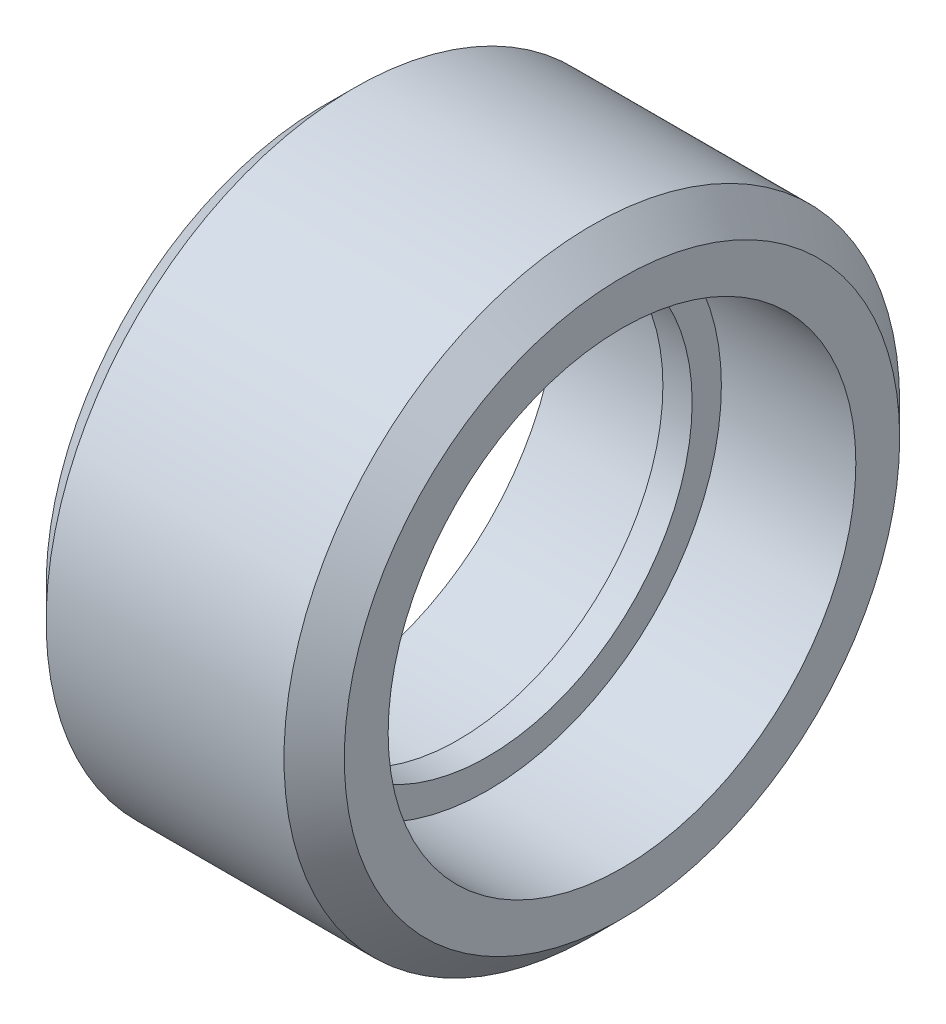
SolidWorks part; units mm, degrees
ref_plane "Front Plane" through (0, 0, 0) normal (0, 0, 1) x (1, 0, 0)
ref_plane "Top Plane" through (0, 0, 0) normal (0, 1, 0) x (1, 0, 0)
ref_plane "Right Plane" through (0, 0, 0) normal (1, 0, 0) x (0, 0, -1)
sketch "Sketch1" plane through (0, 0, 0) normal (0, 0, 1) x (1, 0, 0)
  line L0 (0, 0) -> (0, 8) construction
  line L1 (0, -55) -> (0, 55) construction
  line L2 (0, 7) -> (-0.5, 7)
  line L3 (-0.5, 7) -> (-0.5, 8)
  line L4 (-0.5, 8) -> (-5.1, 8)
  line L5 (-5.1, 8) -> (-5.1, 9.5)
  line L6 (-5.1, 9.5) -> (-4.0686, 10.5314)
  line L7 (-4.0686, 10.5314) -> (0, 10.5314)
  line L8 (0, 10.5314) -> (0, 7)
  line L9 (55, 0) -> (-55, 0) construction
  line L10 (0, 0) -> (-8.8433, 0) construction
  point P5 (0, 7)
  dimension "D1" = 7
  dimension "D2" = 5.1
  dimension "D3" = 4.0686
  dimension "D4" = 45
  dimension "D5" = 8
revolve "Revolve1" add sketch "Sketch1" angle 360 about L10
mirror "Mirror1" about plane through (0, 10.5314, 0) normal (1, 0, 0) of "Revolve1"
scale "Scale1" scale about centroid uniform scaling yes scale factor 1.142857
scale "Scale2" scale about centroid uniform scaling yes scale factor 0.997092
